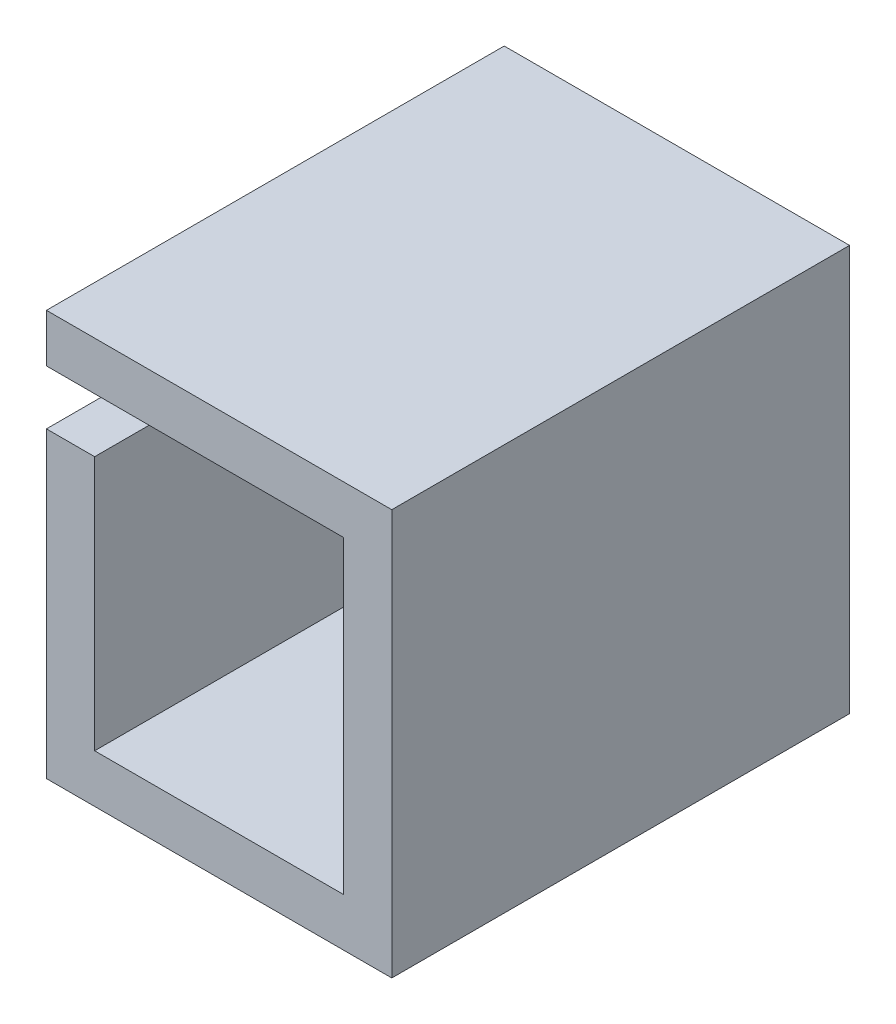
SolidWorks part; units mm, degrees
ref_plane "Front" through (0, 0, 0) normal (0, 0, 1) x (1, 0, 0)
ref_plane "Top" through (0, 0, 0) normal (0, 1, 0) x (1, 0, 0)
ref_plane "Right" through (0, 0, 0) normal (1, 0, 0) x (0, 0, -1)
sketch "Sketch1" plane through (0, 0, 0) normal (0, 0, 1) x (1, 0, 0)
  line L0 (-14.8571, 10) -> (6.6429, 10)
  line L1 (6.6429, 10) -> (6.6429, -15.25)
  line L2 (6.6429, -15.25) -> (-14.8571, -15.25)
  line L3 (-14.8571, -15.25) -> (-14.8571, 3.6071)
  line L4 (-14.8571, 3.6071) -> (-11.8571, 3.6071)
  line L5 (-11.8571, 3.6071) -> (-11.8571, -12.25)
  line L6 (-11.8571, -12.25) -> (3.6429, -12.25)
  line L7 (3.6429, -12.25) -> (3.6429, 7)
  line L8 (3.6429, 7) -> (-14.8571, 7)
  line L9 (-14.8571, 7) -> (-14.8571, 10)
  dimension "D1" = 3
  dimension "D2" = 3
  dimension "D3" = 3
  dimension "D4" = 19.25
  dimension "D5" = 15.5
  dimension "D6" = 3
extrude "Boss-Extrude1" add sketch "Sketch1" along normal blind 25.5
sketch "Sketch2" plane through (0, 0, 0) normal (0, 0, -1) x (-1, 0, 0)
  line L0 (-6.6429, 10) -> (14.8571, 10)
  line L1 (14.8571, 10) -> (14.8571, -15.25)
  line L2 (14.8571, 3.6071) -> (14.8571, -15.25) construction
  line L3 (14.8571, -15.25) -> (-6.6429, -15.25)
  line L4 (-6.6429, -15.25) -> (-6.6429, 10)
extrude "Boss-Extrude2" add sketch "Sketch2" along normal blind 3
